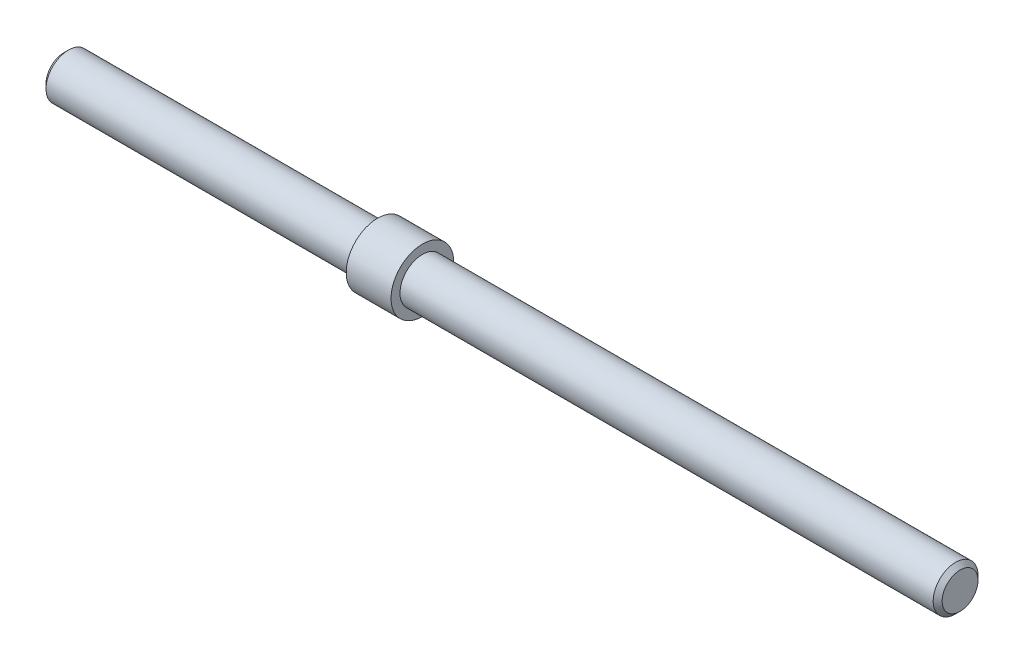
SolidWorks part; units mm, degrees
material "Brass"
ref_plane "Front Plane" through (0, 0, 0) normal (0, 0, 1) x (1, 0, 0)
ref_plane "Top Plane" through (0, 0, 0) normal (0, 1, 0) x (1, 0, 0)
ref_plane "Right Plane" through (0, 0, 0) normal (1, 0, 0) x (0, 0, -1)
sketch "Sketch1" plane through (0, 0, 0) normal (1, 0, 0) x (0, 0, -1)
  circle A0 centre (0, 0) radius 20
  dimension "D1" = 40
extrude "Boss-Extrude1" add sketch "Sketch1" along normal blind 800
chamfer "Chamfer1" distance 4 angle 45 2 edges at (0, 0, -20) (800, 0, -20)
sketch "Sketch2" plane through (0, 0, 0) normal (1, 0, 0) x (0, 0, -1)
  circle A0 centre (0, 0) radius 28
  dimension "D1" = 56
extrude "Boss-Extrude2" add sketch "Sketch2" along normal blind 40 from offset 280
